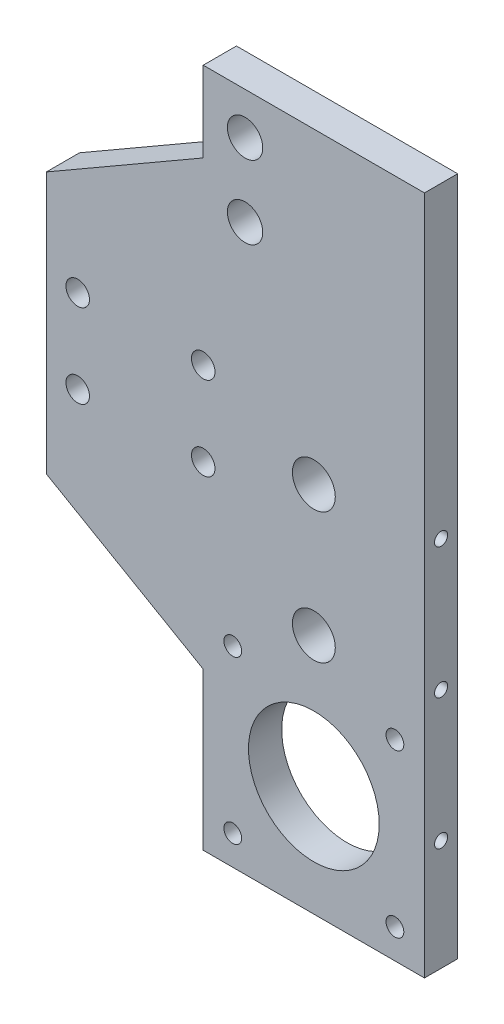
SolidWorks part; units mm, degrees
material "6061 Alloy"
ref_plane "Front Plane" through (0, 0, 0) normal (0, 0, 1) x (1, 0, 0)
ref_plane "Top Plane" through (0, 0, 0) normal (0, 1, 0) x (1, 0, 0)
ref_plane "Right Plane" through (0, 0, 0) normal (1, 0, 0) x (0, 0, -1)
sketch "Sketch2" plane through (0, 0, 0) normal (0, 0, 1) x (1, 0, 0)
  line L0 (0, 0) -> (0, -21.15) construction
  line L1 (-21.15, -21.15) -> (21.15, -21.15)
  line L2 (-21.15, -21.15) -> (-21.15, 108.85)
  line L3 (-21.15, 108.85) -> (21.15, 108.85)
  line L4 (21.15, -21.15) -> (21.15, 108.85)
  circle A0 centre (0, 0) radius 12.5
  circle A1 centre (0, 25) radius 4.1
  circle A2 centre (0, 50) radius 4.1
  dimension "D1" = 25
  dimension "D5" = 25
  dimension "D7" = 8.2
  dimension "D2" = 21.15
  dimension "D3" = 42.3
  dimension "D4" = 130
  dimension "D6" = 25
extrude "Boss-Extrude1" add sketch "Sketch2" along normal blind 6.35
sketch "Sketch3" plane through (21.15, 0, 0) normal (-1, 0, 0) x (0, 0, 1)
  line L0 (6.35, -12.5) -> (6.35, 12.5) construction
  line L1 (6.35, 20.9) -> (6.35, 29.1) construction
  line L2 (6.35, 45.9) -> (6.35, 54.1) construction
  line L3 (6.35, -12.5) -> (6.35, 12.5) construction
  line L4 (6.35, 20.9) -> (6.35, 29.1) construction
  line L5 (6.35, 45.9) -> (6.35, 54.1) construction
  line L6 (3.175, 108.85) -> (3.175, -21.15) construction
  line L7 (6.35, 108.85) -> (0, 108.85) construction
  line L8 (6.35, -21.15) -> (0, -21.15) construction
  line L9 (6.35, 0) -> (3.175, 0) construction
  line L10 (6.35, 25) -> (3.175, 25) construction
  line L11 (6.35, 50) -> (3.175, 50) construction
  point P13 (3.175, 0)
  point P16 (3.175, 25)
  point P18 (3.175, 50)
hole_wizard "Tap Drill for M3x0.5 Tap1" positions "Sketch3" profile "Sketch4" hole size "M3x0.5" standard "ANSI Metric"
sketch "Sketch4" plane through (21.15, 50, 3.175) normal (0, 1, 0) x (0, 0, -1)
  line L0 (0, 0) -> (0, 21.9011)
  line L1 (0, 21.9011) -> (1.25, 21.15)
  line L2 (1.25, 21.15) -> (1.25, 0)
  line L5 (1.25, 0) -> (0, 0)
  line L10 (0, 21.9011) -> (-1.25, 21.15) construction
  line L11 (0, -6.35) -> (0, 107.95) construction
  dimension "Hole Dia." = 2.5
  dimension "Hole Depth" = 21.15
  dimension "Drill Angle" = 118
sketch "Sketch5" plane through (0, 0, 6.35) normal (0, 0, 1) x (1, 0, 0)
  line L1 (-15.5, -15.5) -> (15.5, -15.5) construction
  line L2 (-15.5, -15.5) -> (-15.5, 15.5) construction
  line L3 (-15.5, 15.5) -> (15.5, 15.5) construction
  line L4 (15.5, -15.5) -> (15.5, 15.5) construction
  line L5 (-15.5, -15.5) -> (15.5, 15.5) construction
  line L6 (-15.5, 15.5) -> (15.5, -15.5) construction
  point P0 (0, 0)
  dimension "D1" = 31
hole_wizard "M3 Clearance Hole1" positions "Sketch7" profile "Sketch9" hole size "M3" standard "ANSI Metric" end condition through all
sketch "Sketch7" plane through (0, 0, 6.35) normal (0, 0, 1) x (1, 0, 0)
  point P0 (-15.5, 15.5)
  point P3 (-15.5, -15.5)
  point P6 (15.5, -15.5)
  point P9 (15.5, 15.5)
sketch "Sketch9" plane through (-15.5, 15.5, 6.35) normal (1, 0, 0) x (0, -1, 0)
  line L0 (0, 0) -> (0, 6.35)
  line L1 (0, 6.35) -> (1.7, 6.35)
  line L2 (1.7, 6.35) -> (1.7, 0)
  line L5 (1.7, 0) -> (0, 0)
  line L11 (0, -6.35) -> (0, 107.95) construction
  dimension "Thru Hole Dia." = 3.4
  dimension "Thru Hole Depth" = 6.35
sketch "Sketch11" plane through (0, 0, 6.35) normal (0, 0, 1) x (1, 0, 0)
  line L0 (-13.15, 108.85) -> (-13.15, 78.85) construction
  line L1 (21.15, 108.85) -> (-21.15, 108.85) construction
  line L2 (-13.15, 78.85) -> (-21.15, 78.85) construction
  line L3 (-21.15, 108.85) -> (-21.15, -21.15) construction
  point P7 (-13.15, 100.85)
  point P8 (-13.15, 86.85)
  dimension "D1" = 8
  dimension "D2" = 8
  dimension "D3" = 30
  dimension "D4" = 8
hole_wizard "1/4 Clearance Hole1" positions "Sketch11" profile "Sketch12" hole size "1/4" standard "ANSI Inch" end condition through all
sketch "Sketch12" plane through (-13.15, 86.85, 6.35) normal (1, 0, 0) x (0, -1, 0)
  line L0 (0, 0) -> (0, 6.35)
  line L1 (0, 6.35) -> (3.3782, 6.35)
  line L2 (3.3782, 6.35) -> (3.3782, 0)
  line L5 (3.3782, 0) -> (0, 0)
  line L11 (0, -6.35) -> (0, 107.95) construction
  dimension "Thru Hole Dia." = 6.7564
  dimension "Thru Hole Depth" = 6.35
sketch "Sketch13" plane through (0, 0, 6.35) normal (0, 0, 1) x (1, 0, 0)
  line L0 (-21.15, 8.85) -> (-51.15, 26.1705)
  line L2 (-51.15, 26.1705) -> (-51.15, 76.1705)
  line L3 (-51.15, 76.1705) -> (-21.15, 93.491)
  line L4 (-21.15, 93.491) -> (-21.15, 8.85)
  line L6 (-21.15, 108.85) -> (-21.15, -21.15) construction
  dimension "D1" = 60
  dimension "D2" = 60
  dimension "D3" = 30
  dimension "D4" = 50
  dimension "D5" = 30
extrude "Boss-Extrude2" add sketch "Sketch13" against normal up to surface (6.35 mm away) up to face at (-9.7718, 100.85, 0)
sketch "Sketch14" plane through (0, 0, 6.35) normal (0, 0, 1) x (1, 0, 0)
  line L0 (-51.15, 51.1705) -> (-33.15, 51.1705) construction
  line L1 (-51.15, 76.1705) -> (-51.15, 26.1705) construction
  line L3 (-45.15, 43.1705) -> (-21.15, 43.1705) construction
  line L4 (-45.15, 43.1705) -> (-45.15, 59.1705) construction
  line L5 (-45.15, 59.1705) -> (-21.15, 59.1705) construction
  line L6 (-21.15, 43.1705) -> (-21.15, 59.1705) construction
  line L7 (-45.15, 43.1705) -> (-21.15, 59.1705) construction
  line L8 (-45.15, 59.1705) -> (-21.15, 43.1705) construction
  dimension "D1" = 16
  dimension "D2" = 24
  dimension "D3" = 18
hole_wizard "M4 Clearance Hole1" positions "Sketch15" profile "Sketch16" hole size "M4" standard "ANSI Metric" end condition through all
sketch "Sketch15" plane through (0, 0, 6.35) normal (0, 0, 1) x (1, 0, 0)
  point P0 (-45.15, 59.1705)
  point P3 (-21.15, 59.1705)
  point P6 (-21.15, 43.1705)
  point P9 (-45.15, 43.1705)
sketch "Sketch16" plane through (-45.15, 59.1705, 6.35) normal (1, 0, 0) x (0, -1, 0)
  line L0 (0, 0) -> (0, 6.35)
  line L1 (0, 6.35) -> (2.25, 6.35)
  line L2 (2.25, 6.35) -> (2.25, 0)
  line L5 (2.25, 0) -> (0, 0)
  line L11 (0, -6.35) -> (0, 107.95) construction
  dimension "Thru Hole Dia." = 4.5
  dimension "Thru Hole Depth" = 6.35
